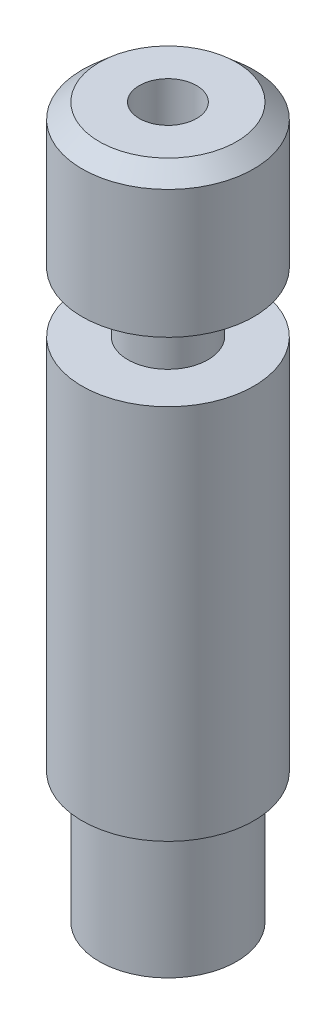
SolidWorks part; units mm, degrees
ref_plane "Front Plane" through (0, 0, 0) normal (0, 0, 1) x (1, 0, 0)
ref_plane "Top Plane" through (0, 0, 0) normal (0, 1, 0) x (1, 0, 0)
ref_plane "Right Plane" through (0, 0, 0) normal (1, 0, 0) x (0, 0, -1)
sketch "Sketch1" plane through (0, 0, 0) normal (0, 0, 1) x (1, 0, 0)
  line L0 (0, 0) -> (1.9, 0) construction
  line L1 (1.9, 0) -> (2.4, 0.2887)
  line L2 (2.4, 0.2887) -> (2.4, 4.5)
  line L3 (2.4, 4.5) -> (3, 4.8464)
  line L4 (3, 4.8464) -> (3, 18)
  line L5 (3, 18) -> (1.4, 18)
  line L6 (1.4, 18) -> (1.4, 20.1)
  line L7 (1.4, 20.1) -> (3, 20.1)
  line L8 (3, 20.1) -> (3, 24.5749)
  line L9 (3, 24.5749) -> (2.4, 25.1)
  line L10 (2.4, 25.1) -> (0, 25.1) construction
  line L11 (0, 25.1) -> (0, 0) construction
  line L12 (1, 25.1) -> (1, 0)
  line L13 (1, 25.1) -> (2.4, 25.1)
  line L14 (2.4, 25.1) -> (2.3615, 25.124)
  line L15 (1, 0) -> (1.9, 0)
  dimension "D1" = 1.9
  dimension "D2" = 2.4
  dimension "D3" = 30
  dimension "D4" = 3
  dimension "D5" = 5
  dimension "D6" = 2.1
  dimension "D7" = 25.1
  dimension "D8" = 0.4
  dimension "D9" = 1
  dimension "D10" = 20.6
revolve "Revolve1" add sketch "Sketch1" angle 360 about L11
equation "\"D2@Sketch1\"=4.8/2"
equation "\"D1@Sketch1\"=3.8/2"
equation "\"D4@Sketch1\"=6/2"
equation "\"D9@Sketch1\"=2/2"
